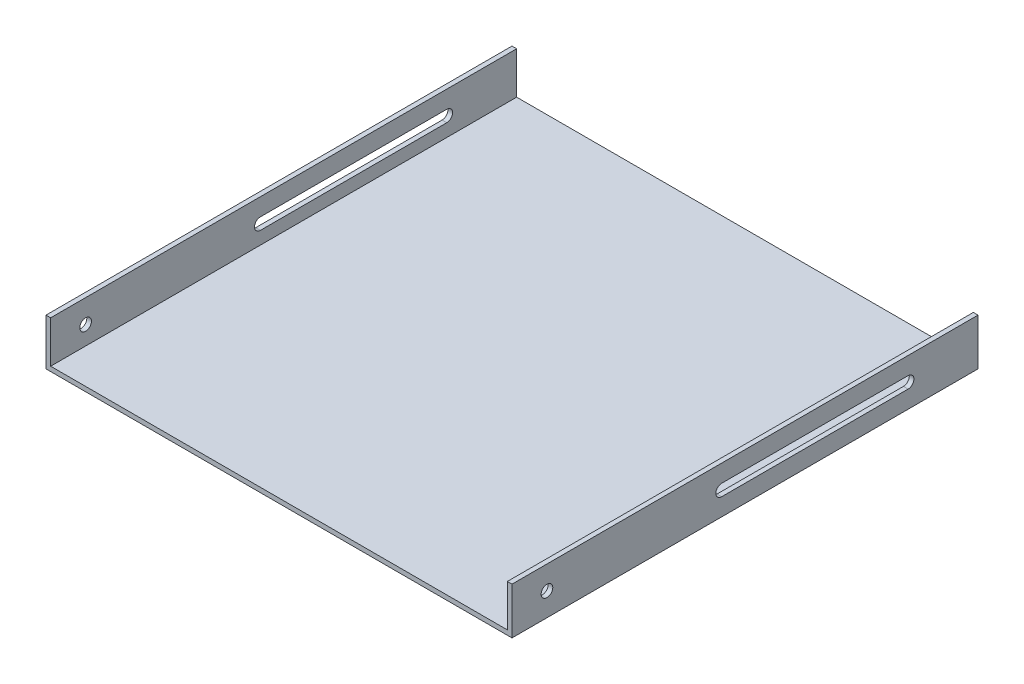
SolidWorks part; units mm, degrees
material "7050-T7651"
ref_plane "Front Plane" through (0, 0, 0) normal (0, 0, 1) x (1, 0, 0)
ref_plane "Top Plane" through (0, 0, 0) normal (0, 1, 0) x (1, 0, 0)
ref_plane "Right Plane" through (0, 0, 0) normal (1, 0, 0) x (0, 0, -1)
sketch "Sketch1" plane through (0, 0, 0) normal (0, 0, 1) x (1, 0, 0)
  line L0 (0, 20) -> (0, 0)
  line L1 (0, 0) -> (200, 0)
  line L2 (200, 0) -> (200, 20)
  line L3 (200, 20) -> (198, 20)
  line L4 (198, 20) -> (198, 2)
  line L5 (198, 2) -> (2, 2)
  line L6 (2, 2) -> (2, 20)
  line L7 (2, 20) -> (0, 20)
  dimension "D1" = 200
  dimension "D2" = 2
  dimension "D3" = 2
  dimension "D4" = 20
  dimension "D5" = 2
extrude "Boss-Extrude1" add sketch "Sketch1" along normal mid plane 200
sketch "Sketch2" plane through (200, 0, 0) normal (1, 0, 0) x (0, 0, -1)
  line L0 (70, 10) -> (-10, 10) construction
  line L1 (70, 7.5) -> (-10, 7.5)
  line L2 (70, 12.5) -> (-10, 12.5)
  line L3 (-100, 0) -> (100, 0) construction
  line L4 (-100, 0) -> (-100, 20) construction
  line L5 (100, 0) -> (100, 20) construction
  circle A0 centre (-85, 10) radius 2.5
  arc A1 (70, 7.5) -> (70, 12.5) centre (70, 10) ccw
  arc A2 (-10, 12.5) -> (-10, 7.5) centre (-10, 10) ccw
  point P4 (30, 10)
  dimension "D1" = 5
  dimension "D2" = 10
  dimension "D3" = 15
  dimension "D4" = 5
  dimension "D5" = 80
  dimension "D6" = 30
extrude "Cut-Extrude1" cut sketch "Sketch2" against normal through all
